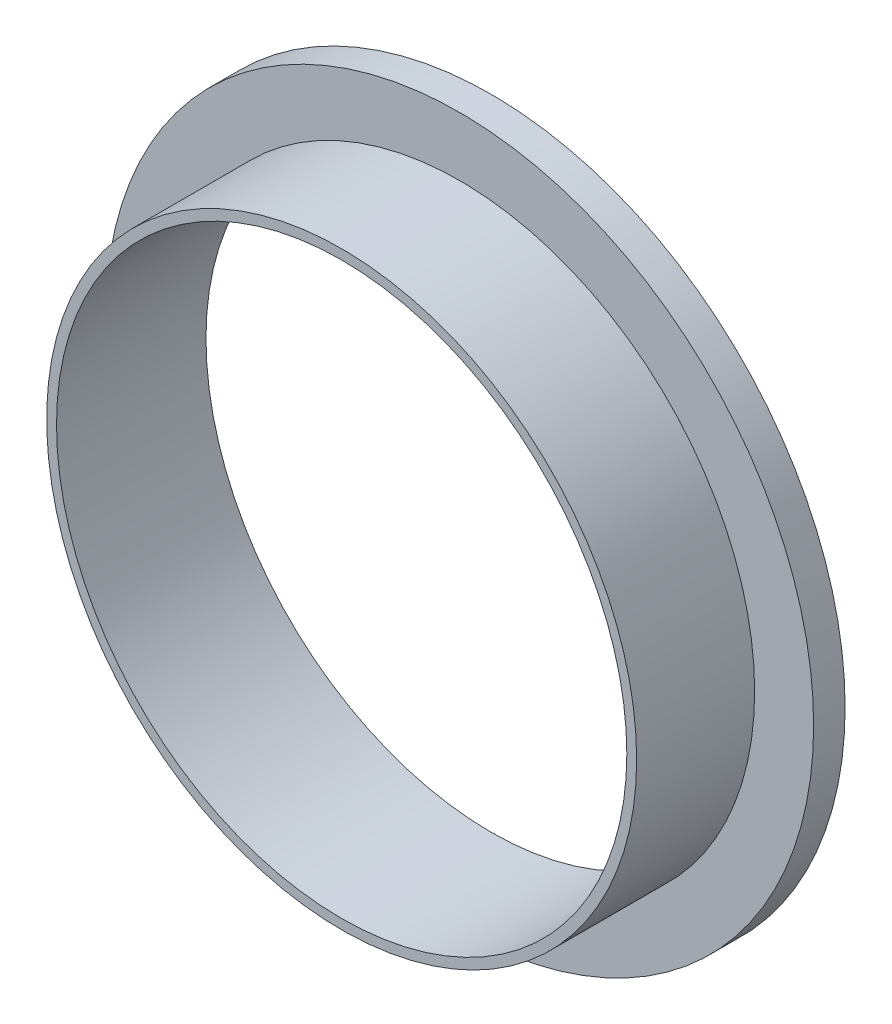
SolidWorks part; units mm, degrees
material "BUTYL"
ref_plane "前视基准面" through (0, 0, 0) normal (0, 0, 1) x (1, 0, 0)
ref_plane "上视基准面" through (0, 0, 0) normal (0, 1, 0) x (1, 0, 0)
ref_plane "右视基准面" through (0, 0, 0) normal (1, 0, 0) x (0, 0, -1)
sketch "草图1" plane through (0, 0, 0) normal (0, 0, 1) x (1, 0, 0)
  circle A0 centre (0, 0) radius 90
  circle A1 centre (0, 0) radius 72.5
  dimension "D1" = 180
  dimension "D2" = 145
extrude "凸台-拉伸1" add sketch "草图1" along normal blind 8
sketch "草图2" plane through (0, 0, 8) normal (0, 0, 1) x (1, 0, 0)
  circle A0 centre (0, 0) radius 75
  circle A1 centre (0, 0) radius 72.5
  dimension "D1" = 150
  dimension "D2" = 145
extrude "凸台-拉伸2" add sketch "草图2" along normal blind 30
